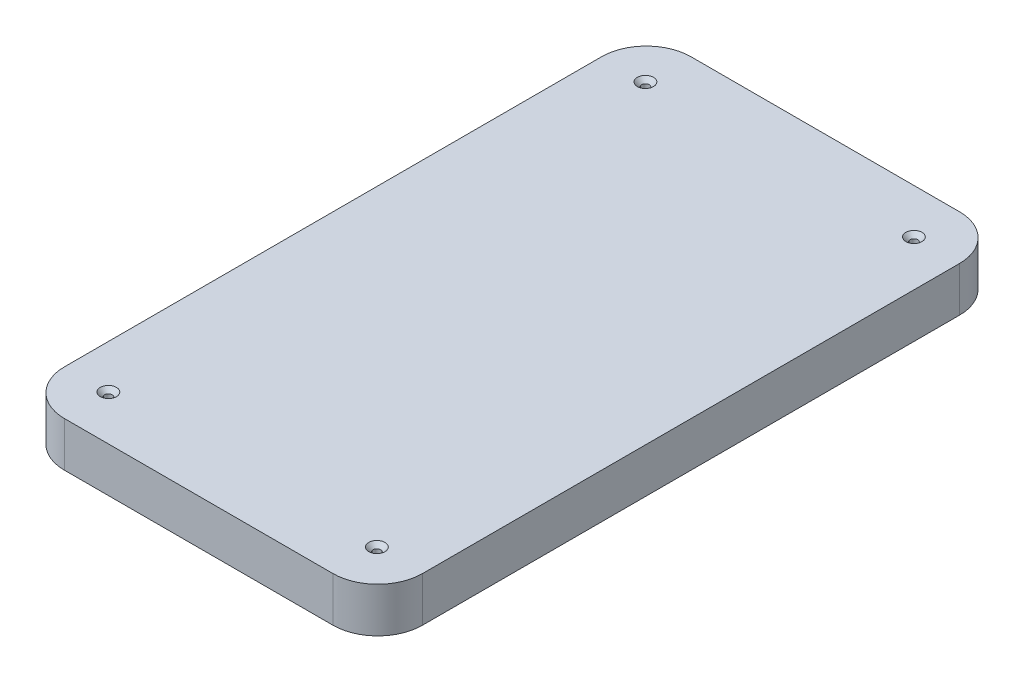
SolidWorks part; units mm, degrees
ref_plane "Front Plane" through (0, 0, 0) normal (0, 0, 1) x (1, 0, 0)
ref_plane "Top Plane" through (0, 0, 0) normal (0, 1, 0) x (1, 0, 0)
ref_plane "Right Plane" through (0, 0, 0) normal (1, 0, 0) x (0, 0, -1)
sketch "Sketch2" plane through (0, 0, 0) normal (0, 1, 0) x (1, 0, 0)
  line L1 (-40, -70) -> (40, -70)
  line L2 (-40, -70) -> (-40, 70)
  line L3 (-40, 70) -> (40, 70)
  line L4 (40, -70) -> (40, 70)
  line L5 (-40, -70) -> (40, 70) construction
  line L6 (-40, 70) -> (40, -70) construction
  point P0 (0, 0)
  dimension "D1" = 80
  dimension "D2" = 140
extrude "Boss-Extrude1" add sketch "Sketch2" along normal blind 10
shell "Shell2" thickness 5
sketch "Sketch6" plane through (0, 0, 0) normal (0, -1, 0) x (1, 0, 0)
  line L0 (-30, 55) -> (-35, 55)
  line L1 (-35, -65) -> (-35, 65) construction
  line L2 (-35, 55) -> (-35, 65)
  line L3 (-35, 65) -> (-25, 65)
  line L4 (-35, 65) -> (35, 65) construction
  line L5 (-25, 65) -> (-25, 60)
  line L6 (25, 60) -> (25, 65)
  line L7 (25, 65) -> (35, 65)
  line L8 (35, 65) -> (35, 55)
  line L9 (35, 65) -> (35, -65) construction
  line L10 (35, 55) -> (30, 55)
  line L11 (30, -55) -> (35, -55)
  line L12 (35, -55) -> (35, -65)
  line L13 (35, -65) -> (25, -65)
  line L14 (35, -65) -> (-35, -65) construction
  line L15 (25, -65) -> (25, -60)
  line L16 (-25, -60) -> (-25, -65)
  line L17 (-25, -65) -> (-35, -65)
  line L18 (-35, -65) -> (-35, -55)
  line L19 (-35, -55) -> (-30, -55)
  arc A0 (-30, 55) -> (-25, 60) centre (-30, 60) ccw
  arc A1 (25, 60) -> (30, 55) centre (30, 60) ccw
  arc A2 (25, -60) -> (30, -55) centre (30, -60) cw
  arc A3 (-30, -55) -> (-25, -60) centre (-30, -60) cw
  dimension "D1" = 5
  dimension "D2" = 10
  dimension "D3" = 10
  dimension "D4" = 5
  dimension "D5" = 5
  dimension "D6" = 10
  dimension "D7" = 10
  dimension "D8" = 5
  dimension "D9" = 5
  dimension "D10" = 10
  dimension "D11" = 10
  dimension "D12" = 5
  dimension "D13" = 5
  dimension "D14" = 10
  dimension "D15" = 10
  dimension "D16" = 5
extrude "Boss-Extrude4" add sketch "Sketch6" against normal up to next
fillet "Fillet3" radius 10 4 edges at (-40, 5, -70) (-40, 5, 70) (40, 5, 70) (40, 5, -70)
hole_wizard "CSK for M1.6 Cross Recess Flat Head Screw1" positions "Sketch7" profile "Sketch9" countersink size "M1.6" standard "IS" end condition through all
sketch "Sketch7" plane through (0, 10, 0) normal (0, 1, 0) x (1, 0, 0)
  point P0 (-30.2163, 60.0284)
  point P3 (29.7724, 60.0284)
  point P6 (29.7724, -59.9579)
  point P9 (-30.2163, -59.9579)
sketch "Sketch9" plane through (-30.2163, 10, -60.0284) normal (1, 0, 0) x (0, 0, 1)
  line L0 (0, 0) -> (0, 10)
  line L1 (0, 10) -> (0.85, 10)
  line L2 (0.85, 10) -> (0.85, 0.95)
  line L3 (0.85, 0.95) -> (1.8, 0)
  line L5 (1.8, 0) -> (0, 0)
  line L6 (-0.85, 0.95) -> (-1.8, 0) construction
  line L11 (0, -6.35) -> (0, 107.95) construction
  dimension "Thru Hole Dia." = 1.7
  dimension "Thru Hole Depth" = 10
  dimension "Near C'Sink Dia." = 3.6
  dimension "Near C'Sink Angle" = 90
